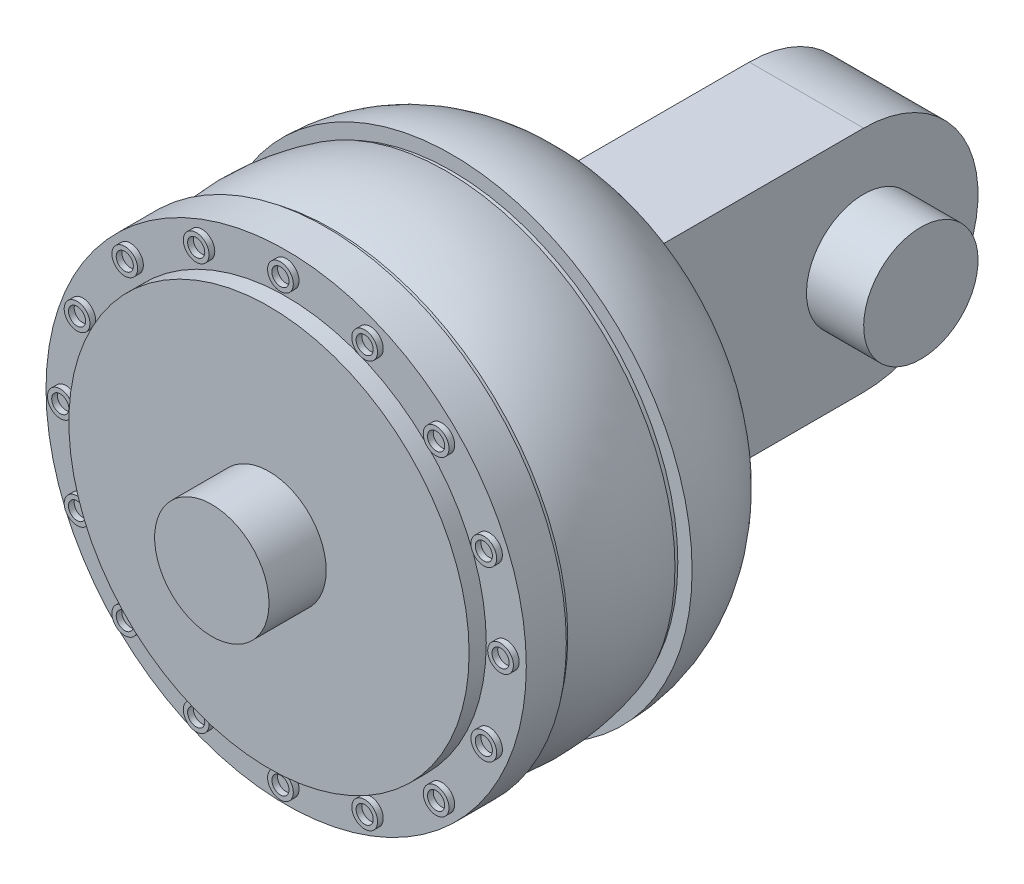
SolidWorks part; units mm, degrees
material "6061-T6 (SS)"
ref_plane "Front Plane" through (0, 0, 0) normal (0, 0, 1) x (1, 0, 0)
ref_plane "Top Plane" through (0, 0, 0) normal (0, 1, 0) x (1, 0, 0)
ref_plane "Right Plane" through (0, 0, 0) normal (1, 0, 0) x (0, 0, -1)
sketch "Sketch1" plane through (0, 0, 0) normal (0, 1, 0) x (1, 0, 0)
  line L0 (0, 0) -> (0, -20)
  line L1 (0, -20) -> (-42, -20)
  line L2 (-32, 0) -> (0, 0)
  arc A0 (-42, -20) -> (-32, 0) centre (-17, -20) cw
  dimension "D3" = 25
  dimension "D1" = 20
  dimension "D2" = 42
revolve "Revolve1" add sketch "Sketch1" angle 360 about L0
sketch "Sketch2" plane through (0, 0, 20) normal (0, 0, 1) x (1, 0, 0)
  circle A0 centre (0, 0) radius 39.5
  dimension "D1" = 79
extrude "Boss-Extrude1" add sketch "Sketch2" along normal blind 1
sketch "Sketch3" plane through (0, 0, 0) normal (0, 1, 0) x (1, 0, 0)
  line L0 (0, -21) -> (-40, -21)
  line L1 (-39.5, -21) -> (39.5, -21) construction
  line L2 (0, -21) -> (0, -41)
  line L3 (0, -41) -> (-40, -41)
  arc A1 (-40, -21) -> (-40, -41) centre (-4.377, -31) ccw
  dimension "D3" = 37
  dimension "D1" = 40
  dimension "D2" = 20
  dimension "D4" = 40
revolve "Revolve2" add sketch "Sketch3" angle 360 about L2
sketch "Sketch4" plane through (0, 0, 41) normal (0, 0, 1) x (1, 0, 0)
  circle A0 centre (0, 0) radius 41.25
  dimension "D1" = 82.5
extrude "Boss-Extrude2" add sketch "Sketch4" along normal blind 1
sketch "Sketch5" plane through (0, 0, 42) normal (0, 0, 1) x (1, 0, 0)
  circle A0 centre (0, 0) radius 42
  dimension "D1" = 84
extrude "Boss-Extrude3" add sketch "Sketch5" along normal blind 7
sketch "Sketch6" plane through (0, 0, 49) normal (0, 0, 1) x (1, 0, 0)
  circle A0 centre (0, 0) radius 35
  dimension "D1" = 70
extrude "Boss-Extrude4" add sketch "Sketch6" along normal blind 3
sketch "Sketch7" plane through (0, 0, 49) normal (0, 0, 1) x (1, 0, 0)
  line L0 (35, 0) -> (42, 0) construction
  circle A0 centre (0, 0) radius 35 construction
  circle A1 centre (0, 0) radius 35 construction
  circle A2 centre (0, 0) radius 42 construction
  circle A3 centre (38.5, 0) radius 2.25
  circle A4 centre (38.5, 0) radius 1.5
  dimension "D1" = 4.5
  dimension "D2" = 3
extrude "Boss-Extrude5" add sketch "Sketch7" along normal blind 1
pattern_circular "CirPattern1" count 16 over 360 about axis through (0, 0, 0) along (0, 0, 1) of "Boss-Extrude5"
sketch "Sketch8" plane through (0, 0, 0) normal (0, 0, -1) x (-1, 0, 0)
  line L1 (-10, 20) -> (10, 20)
  line L2 (-10, 20) -> (-10, -20)
  line L3 (-10, -20) -> (10, -20)
  line L4 (10, 20) -> (10, -20)
  line L5 (-10, 20) -> (10, -20) construction
  line L6 (-10, -20) -> (10, 20) construction
  point P0 (0, 0)
  dimension "D1" = 40
  dimension "D2" = 20
extrude "Boss-Extrude6" add sketch "Sketch8" along normal blind 42
sketch "Sketch9" plane through (-10, 0, 0) normal (-1, 0, 0) x (0, 0, 1)
  line L0 (-42, -20) -> (-42, 20) construction
  circle A0 centre (-42, 0) radius 20
extrude "Boss-Extrude7" add sketch "Sketch9" against normal up to surface (20 mm away) up to face at (10, 0, -21)
sketch "Sketch10" plane through (-10, 0, 0) normal (-1, 0, 0) x (0, 0, 1)
  circle A0 centre (-42, 0) radius 10
  dimension "D1" = 20
extrude "Boss-Extrude8" add sketch "Sketch10" along normal blind 10
sketch "Sketch11" plane through (0, 0, 52) normal (0, 0, 1) x (1, 0, 0)
  circle A0 centre (0, 0) radius 10
  dimension "D1" = 20
extrude "Boss-Extrude9" add sketch "Sketch11" along normal blind 10
mirror "Mirror1" about plane through (0, 0, 0) normal (1, 0, 0) of "Boss-Extrude8"
